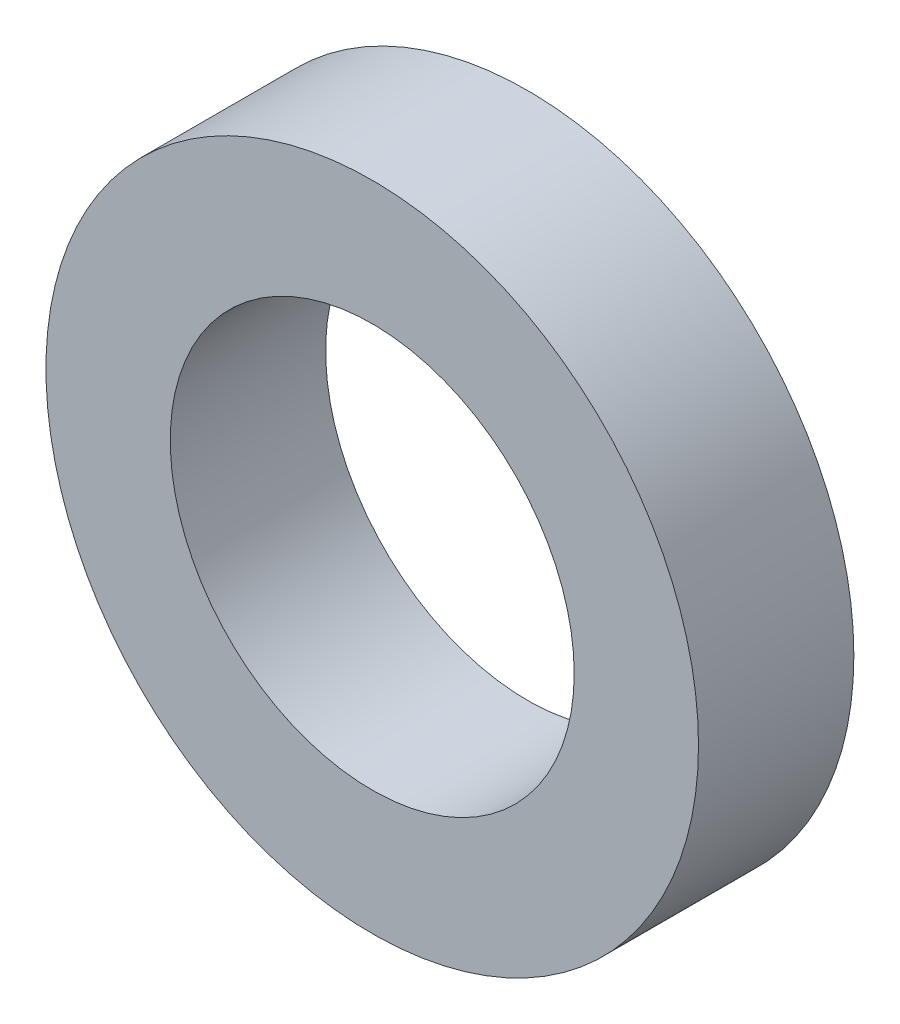
SolidWorks part; units mm, degrees
ref_plane "FRONT" through (0, 0, 0) normal (0, 0, 1) x (1, 0, 0)
ref_plane "TOP" through (0, 0, 0) normal (0, 1, 0) x (1, 0, 0)
ref_plane "RIGHT" through (0, 0, 0) normal (1, 0, 0) x (0, 0, -1)
sketch "Эскиз2" plane through (0, 0, 0) normal (0, 0, 1) x (1, 0, 0)
  circle A0 centre (0, 0) radius 6500
  circle A1 centre (0, 0) radius 10500
extrude "Бобышка-Вытянуть1" add sketch "Эскиз2" along normal blind 5000
